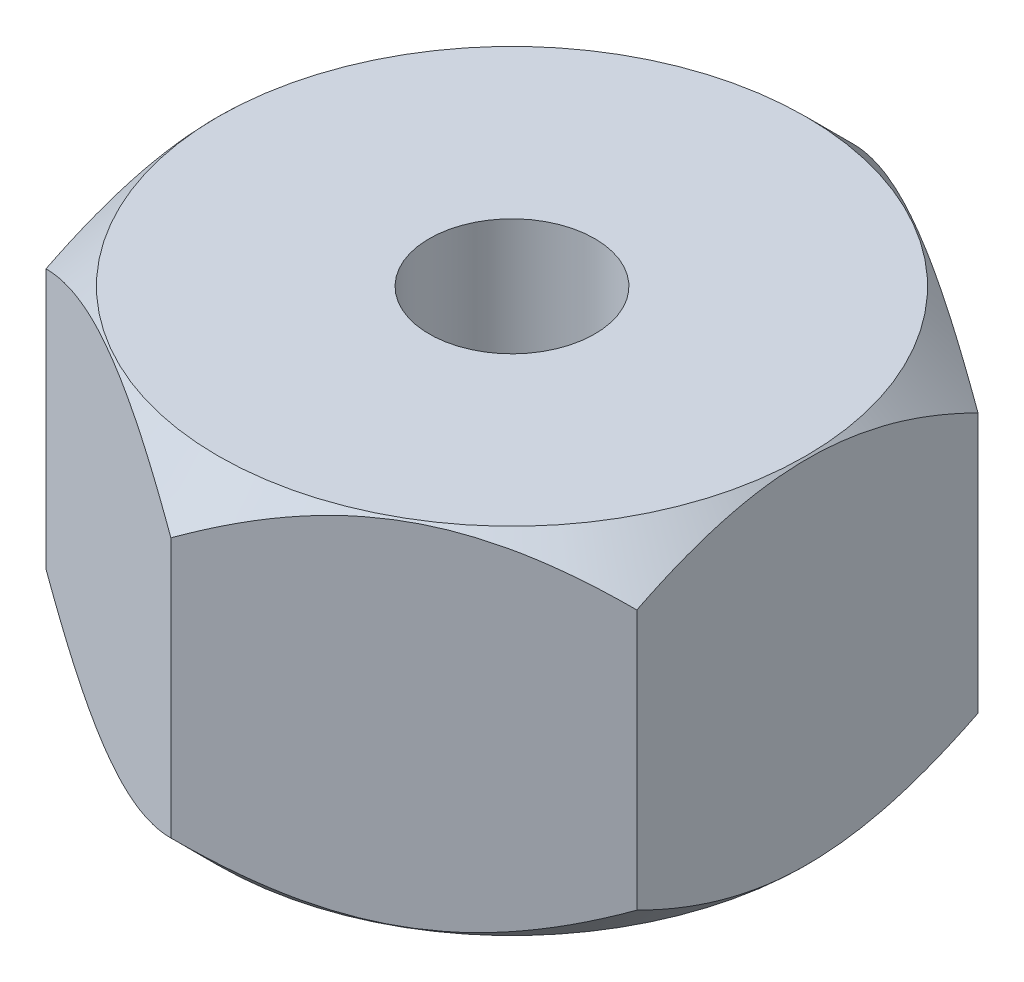
SolidWorks part; units mm, degrees
ref_plane "Front Plane" through (0, 0, 0) normal (0, 0, 1) x (1, 0, 0)
ref_plane "Top Plane" through (0, 0, 0) normal (0, 1, 0) x (1, 0, 0)
ref_plane "Right Plane" through (0, 0, 0) normal (1, 0, 0) x (0, 0, -1)
sketch "Sketch2" plane through (0, 0, 0) normal (0, 1, 0) x (1, 0, 0)
  line L1 (0, 14.4338) -> (-12.5, 7.2169)
  line L2 (-12.5, 7.2169) -> (-12.5, -7.2169)
  line L3 (-12.5, -7.2169) -> (0, -14.4338)
  line L4 (0, -14.4338) -> (12.5, -7.2169)
  line L5 (12.5, -7.2169) -> (12.5, 7.2169)
  line L6 (12.5, 7.2169) -> (0, 14.4338)
  circle A0 centre (0, 0) radius 12.5 construction
  dimension "D1" = 25
extrude "Boss-Extrude1" add sketch "Sketch2" along normal blind 15
sketch "Sketch3" plane through (0, 0, 0) normal (1, 0, 0) x (0, 0, -1)
  line L0 (14.4338, 15) -> (12.4338, 15)
  line L1 (7.2169, 15) -> (14.4338, 15) construction
  line L2 (12.4338, 15) -> (14.4338, 13)
  line L3 (14.4338, 15) -> (14.4338, 0) construction
  line L4 (14.4338, 13) -> (14.4338, 15)
  line L5 (0, 0) -> (0, 18.094) construction
  dimension "D1" = 2
  dimension "D2" = 2
revolve "Cut-Revolve1" cut sketch "Sketch3" angle 360 about L5
ref_plane "Plane1" through (0, 7.5, 0) normal (0, 1, 0) x (1, 0, 0)
mirror "Mirror1" about plane through (0, 7.5, 0) normal (0, 1, 0) of "Cut-Revolve1"
sketch "Sketch5" plane through (0, 0, 0) normal (0, -1, 0) x (1, 0, 0)
  circle A0 centre (0, 0) radius 3.5
  dimension "D1" = 7
extrude "Cut-Extrude2" cut sketch "Sketch5" against normal up to next
sketch "Sketch8" plane through (0, 0, 0) normal (0, -1, 0) x (1, 0, 0)
  circle A0 centre (0, 0) radius 7.75
  dimension "D1" = 15.5
extrude "Cut-Extrude3" cut sketch "Sketch8" against normal blind 10
cosmetic thread "Cosmetic Thread1" parameters "D2"=18
